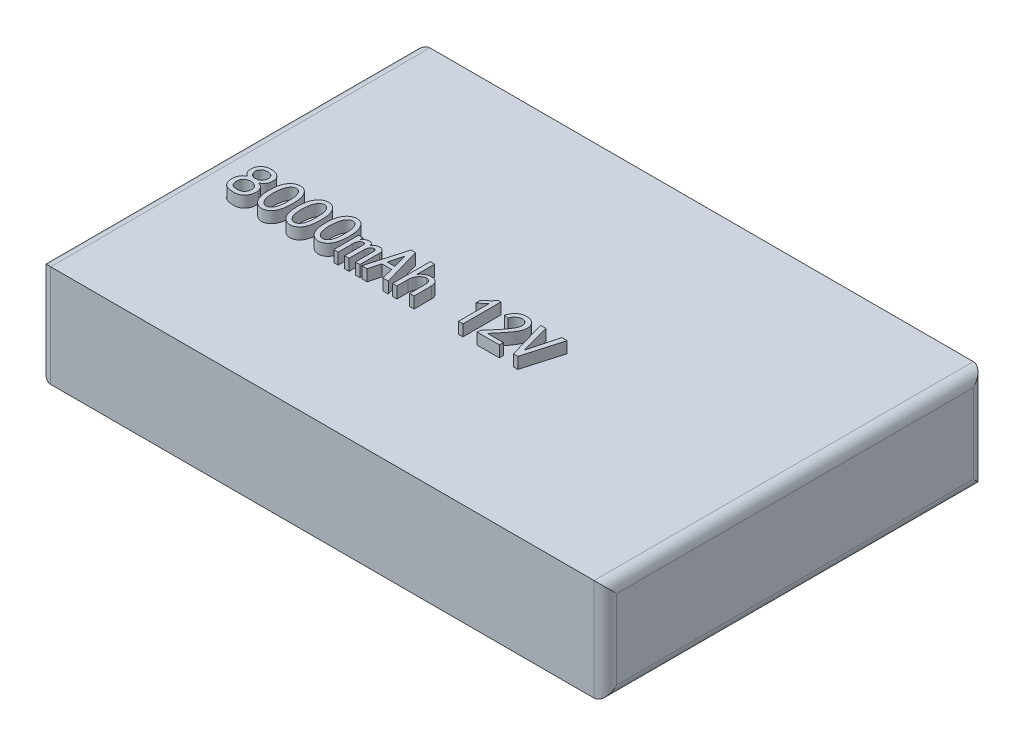
SolidWorks part; units mm, degrees
material "镍"
ref_plane "前视基准面" through (0, 0, 0) normal (0, 0, 1) x (1, 0, 0)
ref_plane "上视基准面" through (0, 0, 0) normal (0, 1, 0) x (1, 0, 0)
ref_plane "右视基准面" through (0, 0, 0) normal (1, 0, 0) x (0, 0, -1)
sketch "草图1" plane through (0, 0, 0) normal (0, 1, 0) x (1, 0, 0)
  line L1 (0, 0) -> (100, 0)
  line L2 (0, 0) -> (0, 67)
  line L3 (0, 67) -> (100, 67)
  line L4 (100, 0) -> (100, 67)
  dimension "D1" = 100
  dimension "D2" = 67
extrude "凸台-拉伸1" add sketch "草图1" along normal blind 18
fillet "圆角1" radius 2 8 edges at (0, 9, -67) (0, 18, -33.5) (0, 9, 0) (0, 0, -33.5) (100, 9, 0) (100, 18, -33.5) (100, 9, -67) (100, 0, -33.5)
sketch "草图3" plane through (0, 18, 0) normal (0, 1, 0) x (1, 0, 0)
  text T0 "8000mAh 12V" font "黑体" height in points 22
extrude "凸台-拉伸2" add sketch "草图3" along normal blind 2
